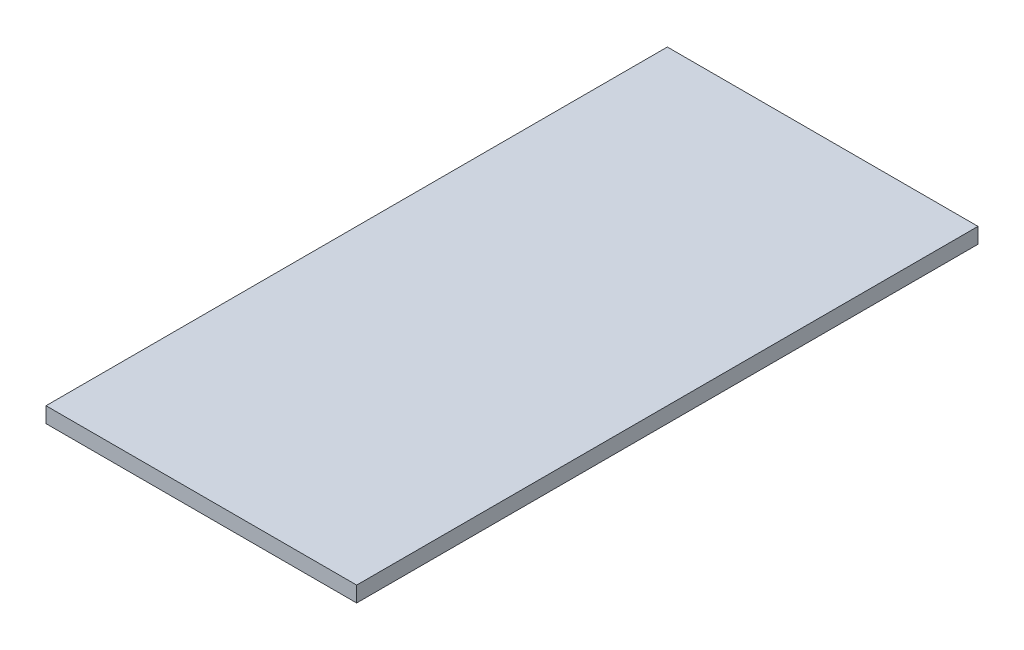
SolidWorks part; units mm, degrees
ref_plane "Front Plane" through (0, 0, 0) normal (0, 0, 1) x (1, 0, 0)
ref_plane "Top Plane" through (0, 0, 0) normal (0, 1, 0) x (1, 0, 0)
ref_plane "Right Plane" through (0, 0, 0) normal (1, 0, 0) x (0, 0, -1)
sketch "Sketch1" plane through (0, 0, 0) normal (0, 1, 0) x (1, 0, 0)
  line L1 (0, 0) -> (50.8, 0)
  line L2 (0, 0) -> (0, 101.6)
  line L3 (0, 101.6) -> (50.8, 101.6)
  line L4 (50.8, 0) -> (50.8, 101.6)
  dimension "D1" = 50.8
  dimension "D2" = 101.6
extrude "Boss-Extrude1" add sketch "Sketch1" along normal blind 2.54
